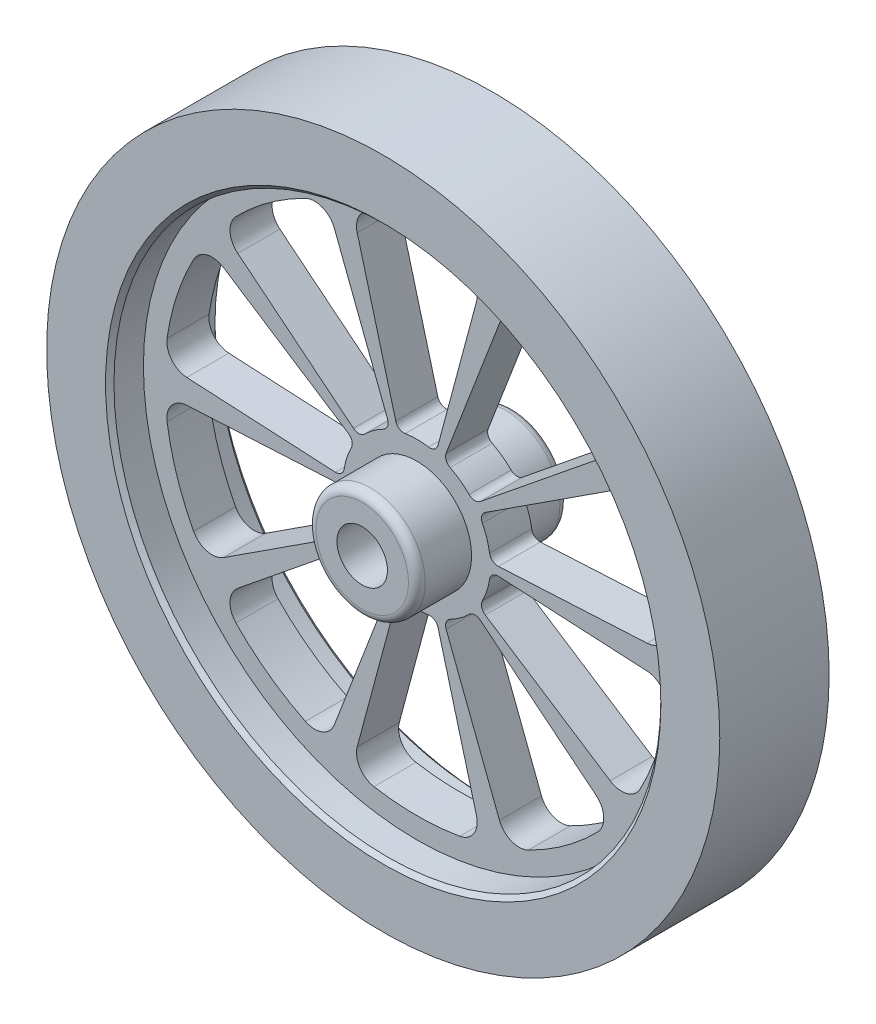
SolidWorks part; units mm, degrees
ref_plane "Front Plane" through (0, 0, 0) normal (0, 0, 1) x (1, 0, 0)
ref_plane "Top Plane" through (0, 0, 0) normal (0, 1, 0) x (1, 0, 0)
ref_plane "Right Plane" through (0, 0, 0) normal (1, 0, 0) x (0, 0, -1)
sketch "Sketch1" plane through (0, 0, 0) normal (0, 0, 1) x (1, 0, 0)
  line L0 (0, 80) -> (0, 0) construction
  line L1 (14.1761, 52.9059) -> (5.0204, 18.7362)
  line L2 (-14.1761, 52.9059) -> (-5.0204, 18.7362)
  line L3 (-4.5293, 16.9037) -> (4.5293, 16.9037) construction
  line L4 (19.6286, 51.1343) -> (6.9513, 18.1088)
  line L5 (42.566, 34.4693) -> (15.0744, 12.207)
  line L6 (45.9359, 29.8311) -> (16.2678, 10.5645)
  line L7 (54.6972, 2.8666) -> (19.3706, 1.0152)
  line L8 (54.6972, -2.8666) -> (19.3706, -1.0152)
  line L9 (45.9359, -29.8311) -> (16.2678, -10.5645)
  line L10 (42.566, -34.4693) -> (15.0744, -12.207)
  line L11 (19.6286, -51.1343) -> (6.9513, -18.1088)
  line L12 (14.1761, -52.9059) -> (5.0204, -18.7362)
  line L13 (-14.1761, -52.9059) -> (-5.0204, -18.7362)
  line L14 (-19.6286, -51.1343) -> (-6.9513, -18.1088)
  line L15 (-42.566, -34.4693) -> (-15.0744, -12.207)
  line L16 (-45.9359, -29.8311) -> (-16.2678, -10.5645)
  line L17 (-54.6972, -2.8666) -> (-19.3706, -1.0152)
  line L18 (-54.6972, 2.8666) -> (-19.3706, 1.0152)
  line L19 (-45.9359, 29.8311) -> (-16.2678, 10.5645)
  line L20 (-42.566, 34.4693) -> (-15.0744, 12.207)
  line L21 (-19.6286, 51.1343) -> (-6.9513, 18.1088)
  circle A0 centre (0, 0) radius 80
  circle A1 centre (0, 0) radius 65
  circle A2 centre (0, 0) radius 6
  circle A3 centre (0, 0) radius 13
  arc A4 (10.1962, 59.1273) -> (-10.1962, 59.1273) centre (0, 0) ccw
  arc A5 (2.7717, 17.2791) -> (-2.7717, 17.2791) centre (0, 0) ccw
  arc A6 (5.0204, 18.7362) -> (2.7717, 17.2791) centre (3.0885, 19.2539) cw
  arc A7 (-5.0204, 18.7362) -> (-2.7717, 17.2791) centre (-3.0885, 19.2539) ccw
  arc A8 (14.1761, 52.9059) -> (10.1962, 59.1273) centre (9.3465, 54.2) ccw
  arc A9 (-14.1761, 52.9059) -> (-10.1962, 59.1273) centre (-9.3465, 54.2) cw
  arc A10 (19.6286, 51.1343) -> (26.5053, 53.8281) centre (24.2965, 49.3425) cw
  arc A11 (43.003, 41.8418) -> (26.5053, 53.8281) centre (0, 0) ccw
  arc A12 (42.566, 34.4693) -> (43.003, 41.8418) centre (39.4194, 38.355) ccw
  arc A13 (6.9513, 18.1088) -> (7.914, 15.6083) centre (8.8185, 17.3921) ccw
  arc A14 (12.3988, 12.3499) -> (7.914, 15.6083) centre (0, 0) ccw
  arc A15 (15.0744, 12.207) -> (12.3988, 12.3499) centre (13.8158, 13.7613) cw
  arc A16 (45.9359, 29.8311) -> (53.0826, 27.9685) centre (48.6591, 25.6378) cw
  arc A17 (59.3842, 8.5742) -> (53.0826, 27.9685) centre (0, 0) ccw
  arc A18 (54.6972, 2.8666) -> (59.3842, 8.5742) centre (54.4355, 7.8597) ccw
  arc A19 (16.2678, 10.5645) -> (15.5769, 7.9756) centre (17.3571, 8.8871) ccw
  arc A20 (17.2899, 2.7035) -> (15.5769, 7.9756) centre (0, 0) ccw
  arc A21 (19.3706, 1.0152) -> (17.2899, 2.7035) centre (19.2659, 3.0124) cw
  arc A22 (54.6972, -2.8666) -> (59.3842, -8.5742) centre (54.4355, -7.8597) cw
  arc A23 (53.0826, -27.9685) -> (59.3842, -8.5742) centre (0, 0) ccw
  arc A24 (45.9359, -29.8311) -> (53.0826, -27.9685) centre (48.6591, -25.6378) ccw
  arc A25 (19.3706, -1.0152) -> (17.2899, -2.7035) centre (19.2659, -3.0124) ccw
  arc A26 (15.5769, -7.9756) -> (17.2899, -2.7035) centre (0, 0) ccw
  arc A27 (16.2678, -10.5645) -> (15.5769, -7.9756) centre (17.3571, -8.8871) cw
  arc A28 (42.566, -34.4693) -> (43.003, -41.8418) centre (39.4194, -38.355) cw
  arc A29 (26.5053, -53.8281) -> (43.003, -41.8418) centre (0, 0) ccw
  arc A30 (19.6286, -51.1343) -> (26.5053, -53.8281) centre (24.2965, -49.3425) ccw
  arc A31 (15.0744, -12.207) -> (12.3988, -12.3499) centre (13.8158, -13.7613) ccw
  arc A32 (7.914, -15.6083) -> (12.3988, -12.3499) centre (0, 0) ccw
  arc A33 (6.9513, -18.1088) -> (7.914, -15.6083) centre (8.8185, -17.3921) cw
  arc A34 (14.1761, -52.9059) -> (10.1962, -59.1273) centre (9.3465, -54.2) cw
  arc A35 (-10.1962, -59.1273) -> (10.1962, -59.1273) centre (0, 0) ccw
  arc A36 (-14.1761, -52.9059) -> (-10.1962, -59.1273) centre (-9.3465, -54.2) ccw
  arc A37 (5.0204, -18.7362) -> (2.7717, -17.2791) centre (3.0885, -19.2539) ccw
  arc A38 (-2.7717, -17.2791) -> (2.7717, -17.2791) centre (0, 0) ccw
  arc A39 (-5.0204, -18.7362) -> (-2.7717, -17.2791) centre (-3.0885, -19.2539) cw
  arc A40 (-19.6286, -51.1343) -> (-26.5053, -53.8281) centre (-24.2965, -49.3425) cw
  arc A41 (-43.003, -41.8418) -> (-26.5053, -53.8281) centre (0, 0) ccw
  arc A42 (-42.566, -34.4693) -> (-43.003, -41.8418) centre (-39.4194, -38.355) ccw
  arc A43 (-6.9513, -18.1088) -> (-7.914, -15.6083) centre (-8.8185, -17.3921) ccw
  arc A44 (-12.3988, -12.3499) -> (-7.914, -15.6083) centre (0, 0) ccw
  arc A45 (-15.0744, -12.207) -> (-12.3988, -12.3499) centre (-13.8158, -13.7613) cw
  arc A46 (-45.9359, -29.8311) -> (-53.0826, -27.9685) centre (-48.6591, -25.6378) cw
  arc A47 (-59.3842, -8.5742) -> (-53.0826, -27.9685) centre (0, 0) ccw
  arc A48 (-54.6972, -2.8666) -> (-59.3842, -8.5742) centre (-54.4355, -7.8597) ccw
  arc A49 (-16.2678, -10.5645) -> (-15.5769, -7.9756) centre (-17.3571, -8.8871) ccw
  arc A50 (-17.2899, -2.7035) -> (-15.5769, -7.9756) centre (0, 0) ccw
  arc A51 (-19.3706, -1.0152) -> (-17.2899, -2.7035) centre (-19.2659, -3.0124) cw
  arc A52 (-54.6972, 2.8666) -> (-59.3842, 8.5742) centre (-54.4355, 7.8597) cw
  arc A53 (-53.0826, 27.9685) -> (-59.3842, 8.5742) centre (0, 0) ccw
  arc A54 (-45.9359, 29.8311) -> (-53.0826, 27.9685) centre (-48.6591, 25.6378) ccw
  arc A55 (-19.3706, 1.0152) -> (-17.2899, 2.7035) centre (-19.2659, 3.0124) ccw
  arc A56 (-15.5769, 7.9756) -> (-17.2899, 2.7035) centre (0, 0) ccw
  arc A57 (-16.2678, 10.5645) -> (-15.5769, 7.9756) centre (-17.3571, 8.8871) cw
  arc A58 (-42.566, 34.4693) -> (-43.003, 41.8418) centre (-39.4194, 38.355) cw
  arc A59 (-26.5053, 53.8281) -> (-43.003, 41.8418) centre (0, 0) ccw
  arc A60 (-19.6286, 51.1343) -> (-26.5053, 53.8281) centre (-24.2965, 49.3425) ccw
  arc A61 (-15.0744, 12.207) -> (-12.3988, 12.3499) centre (-13.8158, 13.7613) ccw
  arc A62 (-7.914, 15.6083) -> (-12.3988, 12.3499) centre (0, 0) ccw
  arc A63 (-6.9513, 18.1088) -> (-7.914, 15.6083) centre (-8.8185, 17.3921) cw
  point P13 (0, 16.9037)
  point P145 (0, 0)
  dimension "D1" = 12
  dimension "D2" = 26
  dimension "D3" = 130
  dimension "D4" = 160
  dimension "D5" = 120
  dimension "D6" = 35
  dimension "D9" = 2
  dimension "D10" = 5
  dimension "D7" = 30
  dimension "D8" = 15
  dimension "D11" = 10
extrude "Boss-Extrude1" add sketch "Sketch1" along normal mid plane 10 contours A1 A3 L2 A9 A4 A8 L1 A6 A5 A7 L5 A15 A14 A13 L4 A10 A11 A12 L7 A21 A20 A19 L6 A16 A17 A18 L9 A27 A26 A25 L8 A22 A23 A24 L11 A33 A32 A31 L10 A28 A29 A30 L13 A39 | A0 A1 | A3 A2
sketch "Sketch3" plane through (0, 0, 0) normal (0, 0, 1) x (1, 0, 0)
  circle A0 centre (0, 0) radius 80 construction
  circle A1 centre (0, 0) radius 80
  circle A2 centre (0, 0) radius 13
  circle A3 centre (0, 0) radius 65
  circle A4 centre (0, 0) radius 6 construction
  circle A5 centre (0, 0) radius 6
  dimension "D1" = 130
  dimension "D2" = 26
extrude "Boss-Extrude2" add sketch "Sketch3" along normal mid plane 26 contours A1 A3 | A2 A5
sketch "Sketch5" plane through (0, 0, 0) normal (0, 0, 1) x (1, 0, 0)
  circle A0 centre (0, 0) radius 6 construction
  circle A1 centre (0, 0) radius 6
  circle A2 centre (0, 0) radius 13 construction
  circle A3 centre (0, 0) radius 13
extrude "Boss-Extrude3" add sketch "Sketch5" along normal mid plane 36
sketch "Sketch6" plane through (0, 0, 0) normal (0, 1, 0) x (1, 0, 0)
  line L0 (13, 18) -> (-13, 18) construction
  circle A0 centre (0, 13) radius 2.5
  dimension "D1" = 5
  dimension "D2" = 5
extrude "Cut-Extrude1" cut sketch "Sketch6" against normal up to surface (13 mm away)
chamfer "Chamfer1" distance 1 angle 45 2 edges at (65, 0, 13) (65, 0, -13)
fillet "Fillet1" radius 2 2 edges at (13, 0, 18) (13, 0, -18)
